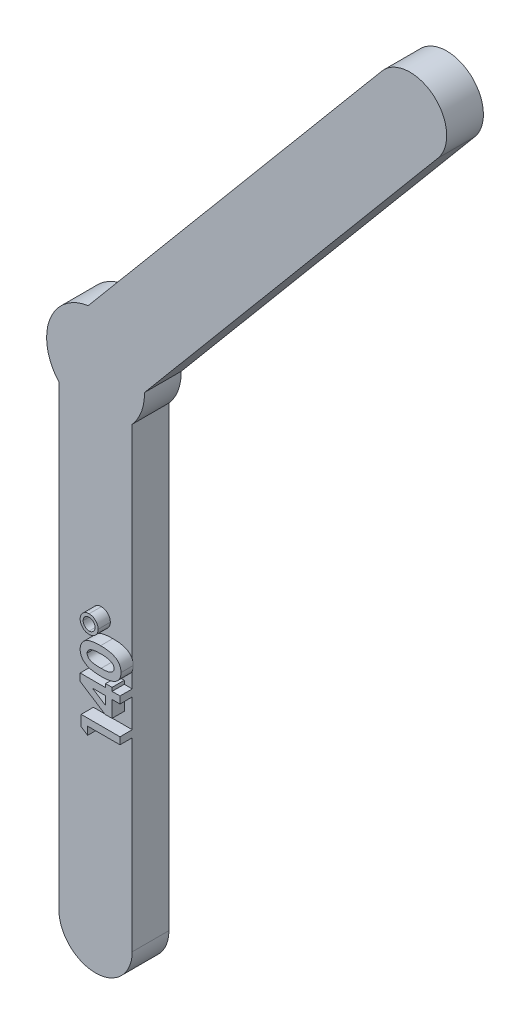
SolidWorks part; units mm, degrees
ref_plane "Front Plane" through (0, 0, 0) normal (0, 0, 1) x (1, 0, 0)
ref_plane "Top Plane" through (0, 0, 0) normal (0, 1, 0) x (1, 0, 0)
ref_plane "Right Plane" through (0, 0, 0) normal (1, 0, 0) x (0, 0, -1)
sketch "Sketch2" plane through (0, 0, 0) normal (0, 0, 1) x (1, 0, 0)
  line L0 (0, 0) -> (0, -40) construction
  line L1 (0, 0) -> (25.7115, 30.6418) construction
  line L2 (23.4134, 32.5701) -> (28.0096, 28.7134) construction
  line L3 (-3, -40) -> (3, -40) construction
  line L4 (-3, -40) -> (-3, -2.6458)
  line L5 (3, -40) -> (3, -2.6458)
  line L6 (23.4134, 32.5701) -> (-0.5975, 3.9551)
  line L7 (28.0096, 28.7134) -> (3.9988, 0.0984)
  arc A0 (-0.5975, 3.9551) -> (-3, -2.6458) centre (0, 0) ccw
  arc A1 (-3, -40) -> (3, -40) centre (0, -40) ccw
  arc A2 (23.4134, 32.5701) -> (28.0096, 28.7134) centre (25.7115, 30.6418) cw
  arc A3 (3, -2.6458) -> (3.9988, 0.0984) centre (0, 0) ccw
  point P12 (25.7115, 30.6418)
  dimension "D3" = 3
  dimension "D4" = 8
  dimension "D1" = 40
  dimension "D2" = 140
extrude "Boss-Extrude1" add sketch "Sketch2" along normal blind 3
sketch "Sketch3" plane through (0, 0, 3) normal (0, 0, 1) x (1, 0, 0)
  text T0 "<b>140°</b>"
extrude "Boss-Extrude2" add sketch "Sketch3" along normal blind 1
